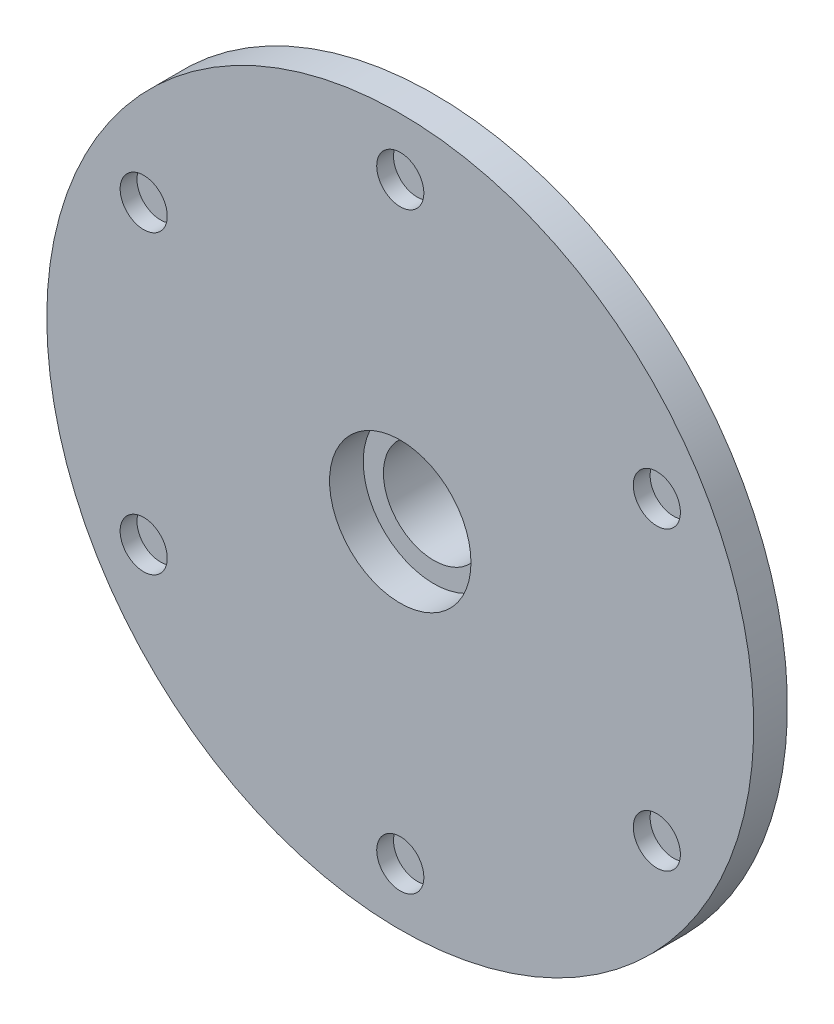
SolidWorks part; units mm, degrees
ref_plane "Front Plane" through (0, 0, 0) normal (0, 0, 1) x (1, 0, 0)
ref_plane "Top Plane" through (0, 0, 0) normal (0, 1, 0) x (1, 0, 0)
ref_plane "Right Plane" through (0, 0, 0) normal (1, 0, 0) x (0, 0, -1)
sketch "Sketch1" plane through (0, 0, 0) normal (0, 0, 1) x (1, 0, 0)
  circle A0 centre (0, 0) radius 52.5
  dimension "D1" = 105
extrude "Boss-Extrude1" add sketch "Sketch1" along normal blind 13
sketch "Sketch2" plane through (0, 0, 0) normal (0, 0, -1) x (-1, 0, 0)
  circle A0 centre (0, 0) radius 17.5
  dimension "D1" = 35
extrude "Boss-Extrude2" add sketch "Sketch2" along normal blind 7
sketch "Sketch3" plane through (0, 0, 0) normal (0, 0, -1) x (-1, 0, 0)
  circle A0 centre (0, 0) radius 52.5 construction
  circle A1 centre (0, 0) radius 52.5
  circle A2 centre (0, 0) radius 25
  dimension "D1" = 50
extrude "Cut-Extrude1" cut sketch "Sketch3" against normal blind 8
sketch "Sketch4" plane through (0, 0, -7) normal (0, 0, -1) x (-1, 0, 0)
  circle A0 centre (0, 0) radius 7.5
  dimension "D1" = 15
extrude "Cut-Extrude2" cut sketch "Sketch4" against normal through all
sketch "Sketch5" plane through (0, 0, 13) normal (0, 0, 1) x (1, 0, 0)
  circle A0 centre (0, 0) radius 10.5
  dimension "D1" = 21
extrude "Cut-Extrude3" cut sketch "Sketch5" against normal blind 5
sketch "Sketch6" plane through (0, 0, 13) normal (0, 0, -1) x (-1, 0, 0)
  circle A0 centre (0, 0) radius 44 construction
  circle A1 centre (0, 44) radius 3.5
  circle A2 centre (38.1051, 22) radius 3.5
  circle A3 centre (38.1051, -22) radius 3.5
  circle A4 centre (0, -44) radius 3.5
  circle A5 centre (-38.1051, -22) radius 3.5
  circle A6 centre (-38.1051, 22) radius 3.5
  point P17 (0, 0)
  dimension "D1" = 88
  dimension "D2" = 7
  dimension "D3" = 6
extrude "Cut-Extrude4" cut sketch "Sketch6" along normal blind 2.5
